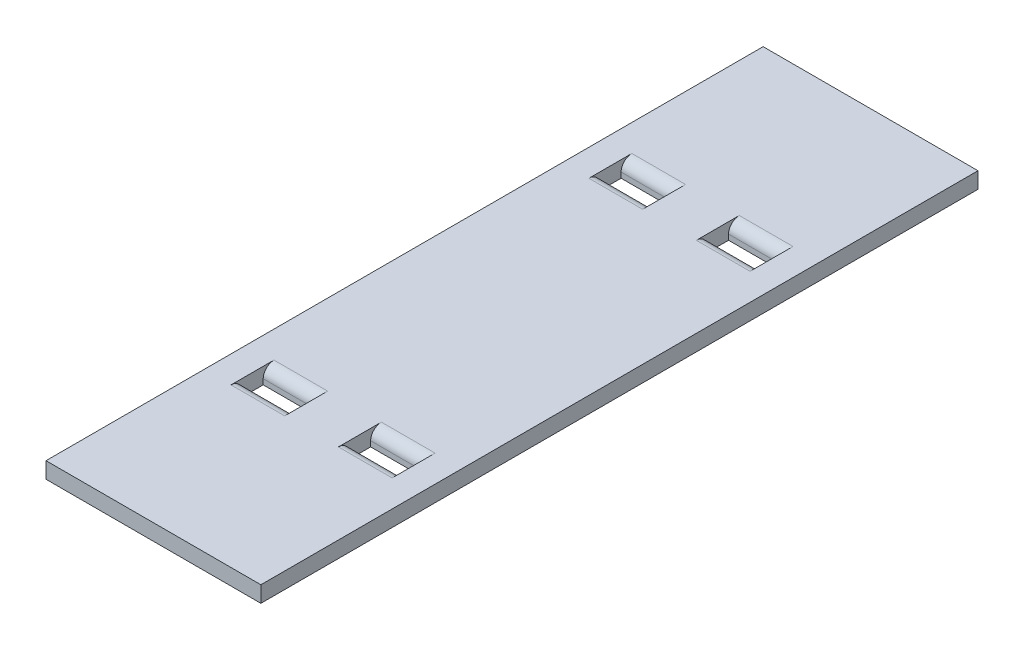
SolidWorks part; units mm, degrees
ref_plane "Front Plane" through (0, 0, 0) normal (0, 0, 1) x (1, 0, 0)
ref_plane "Top Plane" through (0, 0, 0) normal (0, 1, 0) x (1, 0, 0)
ref_plane "Right Plane" through (0, 0, 0) normal (1, 0, 0) x (0, 0, -1)
sketch "Sketch1" plane through (0, 0, 0) normal (0, 1, 0) x (1, 0, 0)
  line L1 (-20, 66.75) -> (20, 66.75)
  line L2 (-20, 66.75) -> (-20, -66.75)
  line L3 (-20, -66.75) -> (20, -66.75)
  line L4 (20, 66.75) -> (20, -66.75)
  line L5 (-20, 66.75) -> (20, -66.75) construction
  line L6 (-20, -66.75) -> (20, 66.75) construction
  point P0 (0, 0)
  dimension "D1" = 40
  dimension "D2" = 133.5
extrude "Boss-Extrude1" add sketch "Sketch1" along normal blind 3
sketch "Sketch2" plane through (0, 0, 0) normal (0, -1, 0) x (1, 0, 0)
  line L0 (0, 66.75) -> (0, 56.75) construction
  line L1 (-20, 66.75) -> (20, 66.75) construction
  line L2 (0, -1.65) -> (0, 1.65) construction
  line L3 (0, 56.75) -> (10, 56.75) construction
  line L4 (1.65, 0) -> (-1.65, 0) construction
  circle A0 centre (10, 56.75) radius 6.11
  circle A1 centre (-10, 56.75) radius 6.11
  circle A2 centre (-10, -56.75) radius 6.11
  circle A3 centre (10, -56.75) radius 6.11
  dimension "D3" = 12.22
  dimension "D1" = 10
  dimension "D2" = 10
extrude "Boss-Extrude2" add sketch "Sketch2" along normal blind 3
sketch "Sketch3" plane through (0, 3, 0) normal (0, 1, 0) x (1, 0, 0)
  line L0 (0, 66.75) -> (0, 33.3125) construction
  line L1 (0, -3.3) -> (0, 3.3) construction
  line L2 (0, 33.3125) -> (10, 33.3125) construction
  line L3 (20, -66.75) -> (20, 66.75) construction
  line L4 (5, 35.3125) -> (15, 35.3125)
  line L5 (5, 35.3125) -> (5, 31.3125)
  line L6 (5, 31.3125) -> (15, 31.3125)
  line L7 (15, 35.3125) -> (15, 31.3125)
  line L8 (5, 35.3125) -> (15, 31.3125) construction
  line L9 (5, 31.3125) -> (15, 35.3125) construction
  line L10 (20, 66.75) -> (-20, 66.75) construction
  line L11 (-5, 31.3125) -> (-15, 31.3125)
  line L12 (-15, 35.3125) -> (-15, 31.3125)
  line L13 (-5, 35.3125) -> (-15, 35.3125)
  line L14 (-5, 35.3125) -> (-5, 31.3125)
  line L16 (-3.3, 0) -> (3.3, 0) construction
  line L17 (-5, -35.3125) -> (-5, -31.3125)
  line L18 (-5, -35.3125) -> (-15, -35.3125)
  line L19 (-15, -35.3125) -> (-15, -31.3125)
  line L20 (-5, -31.3125) -> (-15, -31.3125)
  line L21 (5, -31.3125) -> (15, -31.3125)
  line L22 (15, -35.3125) -> (15, -31.3125)
  line L23 (5, -35.3125) -> (15, -35.3125)
  line L24 (5, -35.3125) -> (5, -31.3125)
  point P17 (0, 66.75)
  dimension "D1" = 33.4375
  dimension "D2" = 10
  dimension "D3" = 10
  dimension "D4" = 4
extrude "Cut-Extrude1" cut sketch "Sketch3" against normal up to next
fillet "Fillet3" radius 1 4 edges at (-10, -3, 62.86) (10, -3, 50.64) (-10, -3, -62.86) (10, -3, -50.64)
fillet "Fillet4" radius 2 8 edges at (-10, 3, 35.3125) (-10, 3, 31.3125) (10, 3, 35.3125) (10, 3, 31.3125) (-10, 3, -31.3125) (-10, 3, -35.3125) (10, 3, -31.3125) (10, 3, -35.3125)
